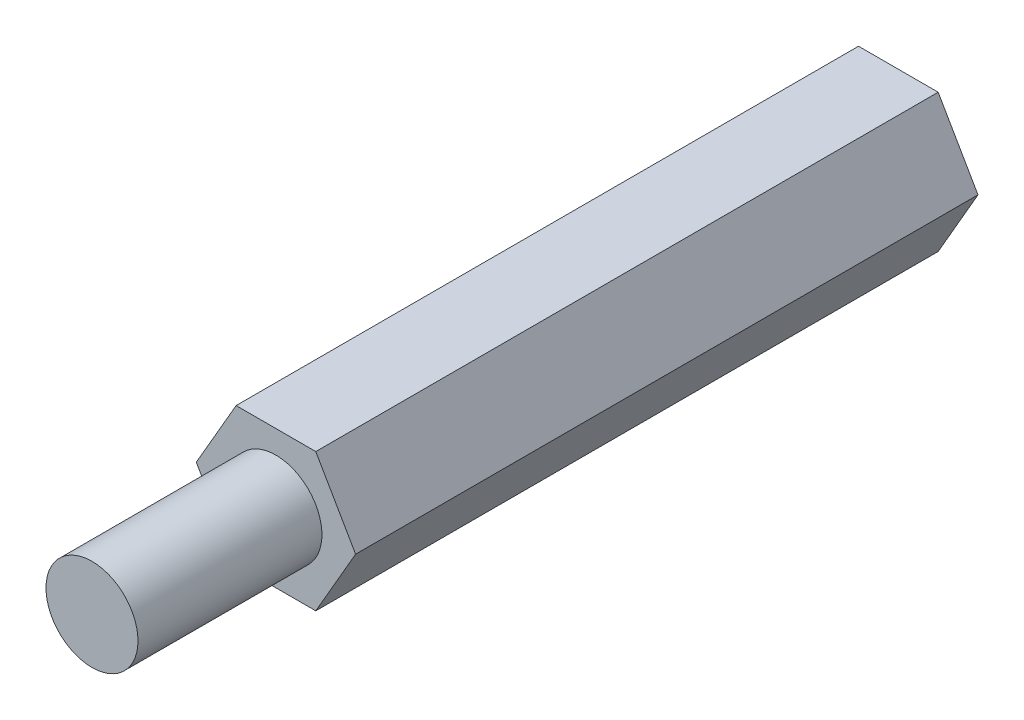
SolidWorks part; units mm, degrees
material "Aluminum"
ref_plane "Front Plane" through (0, 0, 0) normal (0, 0, 1) x (1, 0, 0)
ref_plane "Top Plane" through (0, 0, 0) normal (0, 1, 0) x (1, 0, 0)
ref_plane "Right Plane" through (0, 0, 0) normal (1, 0, 0) x (0, 0, -1)
sketch "Sketch1" plane through (0, 0, 0) normal (0, 0, 1) x (1, 0, 0)
  circle A0 centre (0, 0) radius 1.5
  dimension "D1" = 3
extrude "Boss-Extrude1" add sketch "Sketch1" along normal blind 6
sketch "Sketch2" plane through (0, 0, 0) normal (0, 0, -1) x (-1, 0, 0)
  line L1 (-1.299, 2.25) -> (-2.5981, 0)
  line L2 (-2.5981, 0) -> (-1.299, -2.25)
  line L3 (-1.299, -2.25) -> (1.299, -2.25)
  line L4 (1.299, -2.25) -> (2.5981, 0)
  line L5 (2.5981, 0) -> (1.299, 2.25)
  line L6 (1.299, 2.25) -> (-1.299, 2.25)
  circle A1 centre (0, 0) radius 2.25 construction
  dimension "D2" = 4.5
extrude "Boss-Extrude2" add sketch "Sketch2" along normal blind 20.3
sketch "Sketch3" plane through (0, 0, -20.3) normal (0, 0, -1) x (-1, 0, 0)
  circle A0 centre (0, 0) radius 1.5
  dimension "D1" = 3
extrude "Cut-Extrude1" cut sketch "Sketch3" against normal blind 4.5
